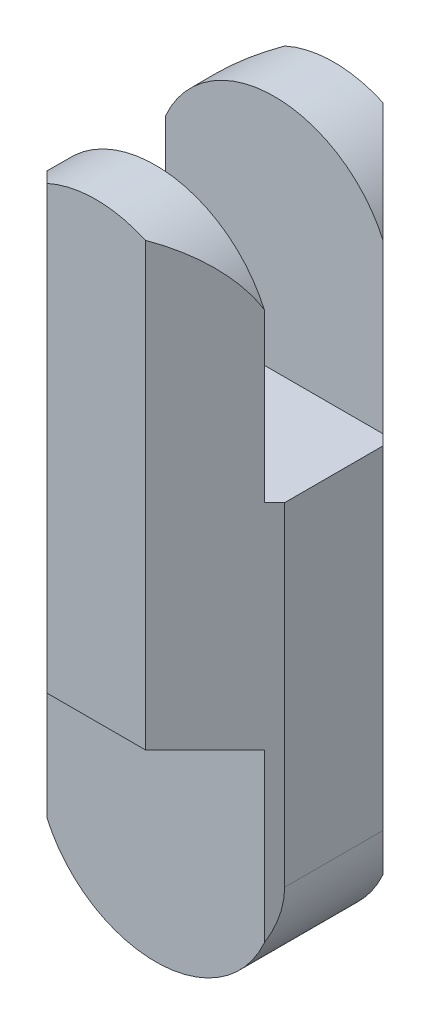
SolidWorks part; units mm, degrees
ref_plane "Front" through (0, 0, 0) normal (0, 0, 1) x (1, 0, 0)
ref_plane "Top" through (0, 0, 0) normal (0, 1, 0) x (1, 0, 0)
ref_plane "Right" through (0, 0, 0) normal (1, 0, 0) x (0, 0, -1)
sketch "草图1" plane through (0, 0, 0) normal (0, 1, 0) x (1, 0, 0)
  line L0 (-12.6518, 0) -> (13.462, 0) construction
  line L1 (0, 11.6722) -> (0, -14.1269) construction
  line L3 (10, 4.1421) -> (4.1421, 10)
  line L4 (4.1421, 10) -> (-4.1421, 10)
  line L5 (-4.1421, 10) -> (-10, 4.1421)
  line L6 (-10, 4.1421) -> (-10, -4.1421)
  line L7 (-10, -4.1421) -> (-4.1421, -10)
  line L8 (-4.1421, -10) -> (4.1421, -10)
  line L9 (4.1421, -10) -> (10, -4.1421)
  line L10 (10, -4.1421) -> (10, 4.1421)
  circle A0 centre (0, 0) radius 10 construction
extrude "凸台-拉伸1" add sketch "草图1" along normal blind 58
sketch "草图2" plane through (0, 0, 10) normal (0, 0, 1) x (1, 0, 0)
  line L0 (0, 0) -> (0, 24) construction
  line L7 (-10, 10) -> (-10, -2.3893)
  line L8 (-10, -2.3893) -> (10, -2.3893)
  line L9 (10, 10) -> (10, -2.3893)
  arc A1 (-10, 10) -> (10, 10) centre (0, 10) ccw
extrude "切除-拉伸1" cut sketch "草图2" against normal blind 66
sketch "草图4" plane through (0, 0, 10) normal (0, 0, 1) x (1, 0, 0)
  line L0 (10, 58) -> (10, 10) construction
  line L2 (-10, 10) -> (-10, 20)
  line L3 (-10, 20) -> (10, 20)
  line L4 (10, 10) -> (10, 20)
  arc A0 (-10, 10) -> (10, 10) centre (0, 10) ccw
extrude "切除-拉伸2" cut sketch "草图4" against normal blind 5
sketch "草图5" plane through (0, 0, -10) normal (0, 0, -1) x (-1, 0, 0)
  line L0 (10, 58) -> (10, 10) construction
  line L2 (-10, 10) -> (-10, 20)
  line L3 (-10, 20) -> (10, 20)
  line L4 (10, 10) -> (10, 20)
  arc A0 (-10, 10) -> (10, 10) centre (0, 10) ccw
extrude "切除-拉伸3" cut sketch "草图5" against normal blind 5
sketch "草图6" plane through (0, 0, 0) normal (0, 0, 1) x (1, 0, 0)
  line L0 (0, 58) -> (0, 0) construction
  line L1 (-4.1421, 58) -> (4.1421, 58) construction
  line L2 (10, 58) -> (10, 10) construction
  line L3 (-10, 58) -> (10, 58)
  line L4 (-10, 58) -> (-10, 38)
  line L5 (-10, 38) -> (10, 38)
  line L6 (10, 58) -> (10, 38)
  dimension "D1" = 20
extrude "切除-拉伸4" cut sketch "草图6" against normal mid plane 10
sketch "草图7" plane through (0, 0, 10) normal (0, 0, 1) x (1, 0, 0)
  line L0 (0, 58) -> (0, 0) construction
  line L1 (-4.1421, 58) -> (4.1421, 58) construction
  line L4 (-10, 48) -> (-10, 63.6612)
  line L5 (-10, 63.6612) -> (10, 63.6612)
  line L6 (10, 48) -> (10, 63.6612)
  arc A0 (10, 48) -> (-10, 48) centre (0, 48) ccw
  point P6 (0, 0)
  point P11 (0, 0)
extrude "切除-拉伸5" cut sketch "草图7" against normal blind 30
